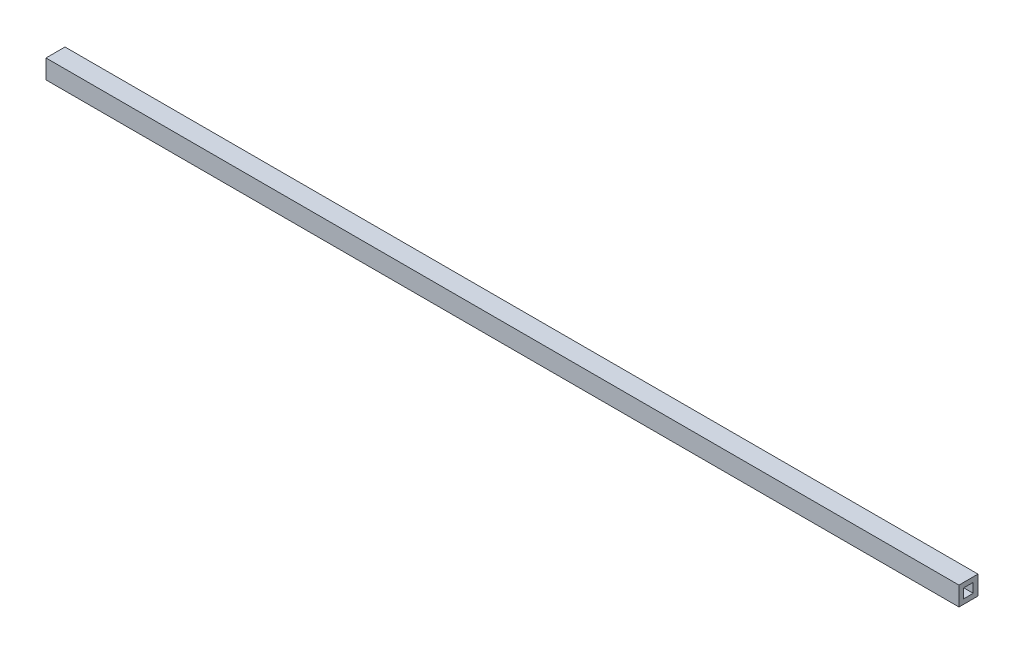
SolidWorks part; units mm, degrees
ref_plane "Front Plane" through (0, 0, 0) normal (0, 0, 1) x (1, 0, 0)
ref_plane "Top Plane" through (0, 0, 0) normal (0, 1, 0) x (1, 0, 0)
ref_plane "Right Plane" through (0, 0, 0) normal (1, 0, 0) x (0, 0, -1)
sketch "Sketch1" plane through (0, 0, 0) normal (0, 0, 1) x (1, 0, 0)
  line L1 (609.6, -12.7) -> (-609.6, -12.7)
  line L2 (609.6, -12.7) -> (609.6, 12.7)
  line L3 (609.6, 12.7) -> (-609.6, 12.7)
  line L4 (-609.6, -12.7) -> (-609.6, 12.7)
  line L5 (609.6, -12.7) -> (-609.6, 12.7) construction
  line L6 (609.6, 12.7) -> (-609.6, -12.7) construction
  point P0 (0, 0)
  dimension "D1" = 1219.2
extrude "Boss-Extrude1" add sketch "Sketch1" along normal blind 25.4
sketch "Sketch2" plane through (609.6, 0, 0) normal (1, 0, 0) x (0, 0, -1)
  line L1 (-6.35, 6.35) -> (-19.05, 6.35)
  line L2 (-6.35, 6.35) -> (-6.35, -6.35)
  line L3 (-6.35, -6.35) -> (-19.05, -6.35)
  line L4 (-19.05, 6.35) -> (-19.05, -6.35)
  line L5 (-6.35, 6.35) -> (-19.05, -6.35) construction
  line L6 (-6.35, -6.35) -> (-19.05, 6.35) construction
  point P0 (-12.7, 0)
  dimension "D1" = 12.7
  dimension "D2" = 12.7
extrude "Cut-Extrude1" cut sketch "Sketch2" against normal through all
equation "\"in1in\"=2.15"
